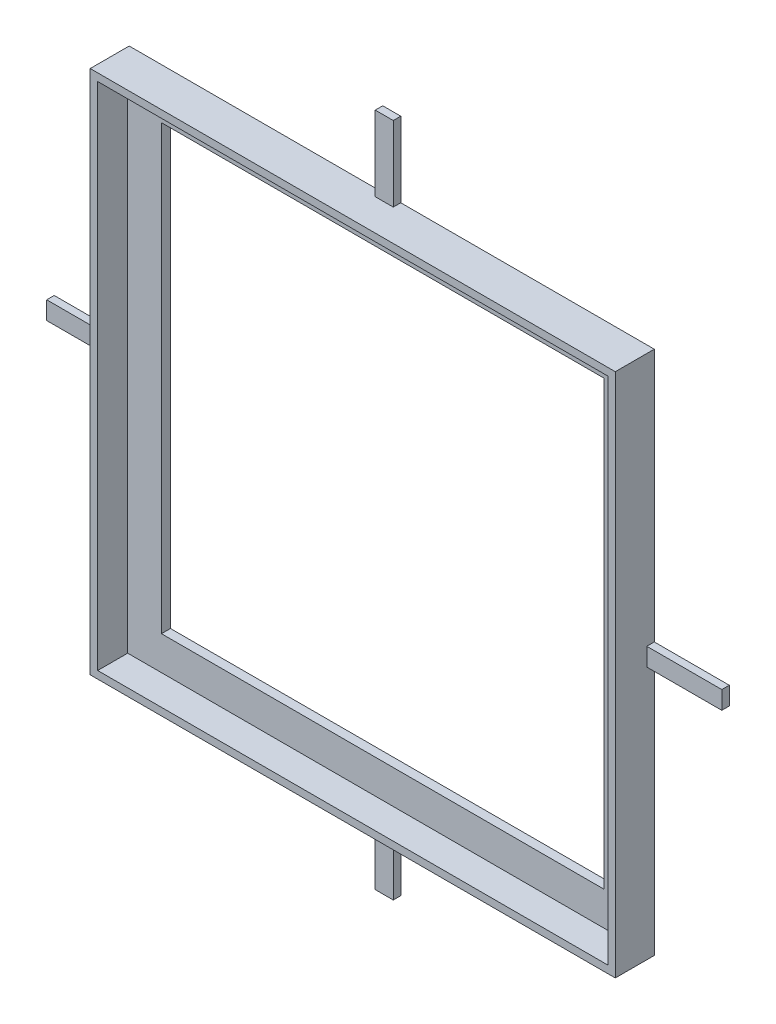
SolidWorks part; units mm, degrees
ref_plane "Plan de face" through (0, 0, 0) normal (0, 0, 1) x (1, 0, 0)
ref_plane "Plan de dessus" through (0, 0, 0) normal (0, 1, 0) x (1, 0, 0)
ref_plane "Plan de droite" through (0, 0, 0) normal (1, 0, 0) x (0, 0, -1)
sketch "Esquisse1" plane through (0, 0, 0) normal (0, 0, 1) x (1, 0, 0)
  line L1 (-175, 175) -> (175, 175)
  line L2 (-175, 175) -> (-175, -175)
  line L3 (-175, -175) -> (175, -175)
  line L4 (175, 175) -> (175, -175)
  line L5 (-175, 175) -> (175, -175) construction
  line L6 (-175, -175) -> (175, 175) construction
  point P0 (0, 0)
  dimension "D1" = 350
  dimension "D2" = 350
extrude "Boss.-Extru.1" add sketch "Esquisse1" along normal blind 26
sketch "Esquisse2" plane through (0, 0, 26) normal (0, 0, 1) x (1, 0, 0)
  line L1 (-147.5, 147.5) -> (147.5, 147.5)
  line L2 (-147.5, 147.5) -> (-147.5, -147.5)
  line L3 (-147.5, -147.5) -> (147.5, -147.5)
  line L4 (147.5, 147.5) -> (147.5, -147.5)
  line L5 (-147.5, 147.5) -> (147.5, -147.5) construction
  line L6 (-147.5, -147.5) -> (147.5, 147.5) construction
  line L7 (-170, 170) -> (170, 170)
  line L8 (-170, 170) -> (-170, -170)
  line L9 (-170, -170) -> (170, -170)
  line L10 (170, 170) -> (170, -170)
  line L11 (-170, 170) -> (170, -170) construction
  line L12 (-170, -170) -> (170, 170) construction
  point P0 (0, 0)
  point P6 (0, 0)
  dimension "D1" = 295
  dimension "D2" = 295
  dimension "D3" = 340
  dimension "D4" = 340
extrude "Enlèv. mat.-Extru.1" cut sketch "Esquisse2" against normal blind 20
sketch "Esquisse3" plane through (0, 0, 26) normal (0, 0, 1) x (1, 0, 0)
  line L0 (-147.5, -147.5) -> (147.5, -147.5) construction
  line L1 (-147.5, 147.5) -> (147.5, 147.5)
  line L2 (-147.5, 147.5) -> (-147.5, -147.5)
  line L3 (-147.5, -147.5) -> (147.5, -147.5)
  line L4 (147.5, 147.5) -> (147.5, -147.5)
  line L5 (-147.5, 147.5) -> (147.5, -147.5) construction
  line L6 (-147.5, -147.5) -> (147.5, 147.5) construction
  point P0 (0, 0)
extrude "Enlèv. mat.-Extru.2" cut sketch "Esquisse3" against normal through all
sketch "Esquisse4" plane through (0, 0, 0) normal (0, 0, 1) x (1, 0, 0)
  line L0 (-175, 175) -> (-175, -175) construction
  line L1 (-225, 6) -> (-175, 6)
  line L2 (-225, 6) -> (-225, -6)
  line L3 (-225, -6) -> (-175, -6)
  line L5 (-225, 6) -> (-175, 0) construction
  line L6 (-225, -6) -> (-175, 0) construction
  line L7 (-175, 6) -> (-175, -6)
  line L8 (0, 0) -> (-175, 0) construction
  line L9 (0, 0) -> (0, 125) construction
  line L11 (225, -6) -> (175, 0) construction
  line L12 (225, 6) -> (175, 0) construction
  line L13 (175, 6) -> (175, -6)
  line L14 (225, -6) -> (175, -6)
  line L15 (225, 6) -> (225, -6)
  line L16 (225, 6) -> (175, 6)
  line L17 (6, 175) -> (-6, 175)
  line L18 (-6, 225) -> (6, 225)
  line L19 (-6, 225) -> (-6, 175)
  line L21 (6, 225) -> (6, 175)
  line L22 (-6, 225) -> (0, 175) construction
  line L23 (0, 175) -> (6, 225) construction
  line L24 (0, -175) -> (6, -225) construction
  line L25 (-6, -225) -> (0, -175) construction
  line L26 (6, -225) -> (6, -175)
  line L27 (-6, -225) -> (-6, -175)
  line L28 (-6, -225) -> (6, -225)
  line L29 (6, -175) -> (-6, -175)
  point P0 (-175, 0)
  point P18 (175, 0)
  dimension "D1" = 12
extrude "Boss.-Extru.2" add sketch "Esquisse4" along normal blind 5
